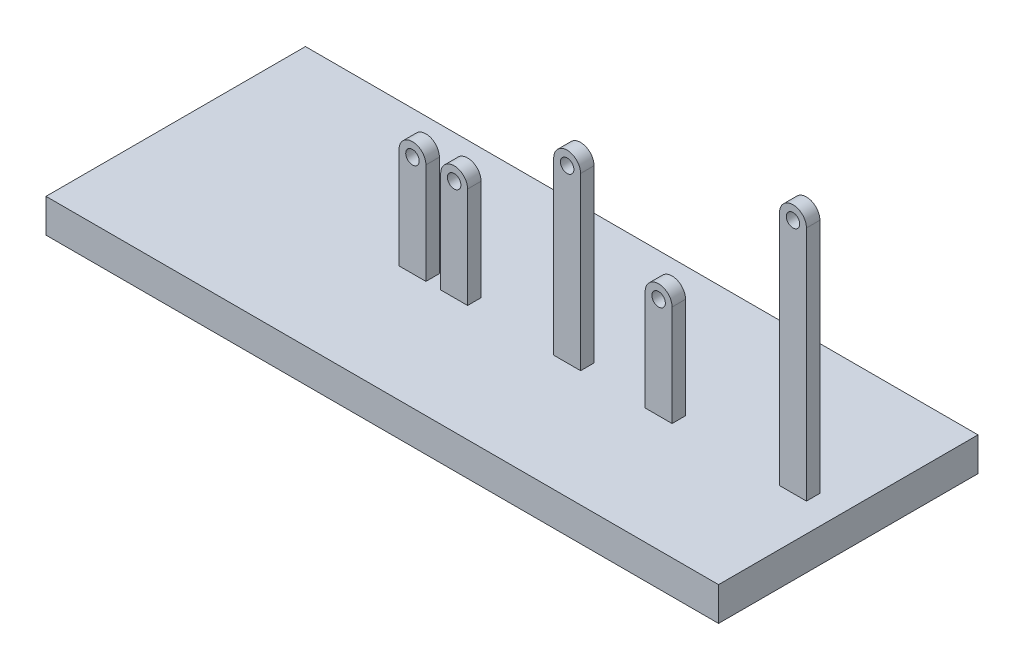
SolidWorks part; units mm, degrees
ref_plane "前基準面" through (0, 0, 0) normal (0, 0, 1) x (1, 0, 0)
ref_plane "上基準面" through (0, 0, 0) normal (0, 1, 0) x (1, 0, 0)
ref_plane "右基準面" through (0, 0, 0) normal (1, 0, 0) x (0, 0, -1)
sketch "草圖1" plane through (0, 0, 0) normal (0, 1, 0) x (1, 0, 0)
  line L1 (50, -19.288) -> (-50, -19.288)
  line L2 (50, -19.288) -> (50, 19.288)
  line L3 (50, 19.288) -> (-50, 19.288)
  line L4 (-50, -19.288) -> (-50, 19.288)
  line L5 (50, -19.288) -> (-50, 19.288) construction
  line L6 (50, 19.288) -> (-50, -19.288) construction
  point P0 (0, 0)
  dimension "D1" = 100
extrude "填料-伸長1" add sketch "草圖1" along normal blind 5
sketch "草圖2" plane through (0, 0, 0) normal (0, 0, 1) x (1, 0, 0)
  line L0 (-8.6, 20) -> (-8.6, 0)
  line L1 (-50, 0) -> (50, 0) construction
  line L2 (-8.6, 0) -> (-4.6, 0)
  line L3 (-4.6, 20) -> (-4.6, 0)
  line L4 (-14.8, 20) -> (-14.8, 0)
  line L5 (-10.8, 20) -> (-10.8, 0)
  line L6 (-14.8, 0) -> (-10.8, 0)
  line L7 (21.8, 20) -> (21.8, 0)
  line L8 (21.8, 0) -> (25.8, 0)
  line L9 (25.8, 20) -> (25.8, 0)
  line L10 (8.2, 30.4) -> (8.2, 0)
  line L11 (8.2, 0) -> (12.2, 0)
  line L12 (12.2, 30.4) -> (12.2, 0)
  line L13 (41.78, 40.17) -> (41.78, 0)
  line L14 (41.78, 0) -> (45.78, 0)
  line L15 (45.78, 40.17) -> (45.78, 0)
  arc A0 (-4.6, 20) -> (-8.6, 20) centre (-6.6, 20) ccw
  circle A1 centre (-6.6, 20) radius 1
  arc A2 (-10.8, 20) -> (-14.8, 20) centre (-12.8, 20) ccw
  circle A3 centre (-12.8, 20) radius 1
  arc A4 (25.8, 20) -> (21.8, 20) centre (23.8, 20) ccw
  circle A5 centre (23.8, 20) radius 1
  arc A6 (12.2, 30.4) -> (8.2, 30.4) centre (10.2, 30.4) ccw
  circle A7 centre (10.2, 30.4) radius 1
  arc A8 (45.78, 40.17) -> (41.78, 40.17) centre (43.78, 40.17) ccw
  circle A9 centre (43.78, 40.17) radius 1
  point P9 (0, 0)
  point P16 (-12.8, 15.1746)
  point P17 (-19.6112, 30.3883)
  point P24 (23.8, 0)
  point P38 (45.7681, 20.17)
  point P39 (41.6151, -0.2261)
  point P41 (10.2, 25.392)
  dimension "D1" = 2
  dimension "D2" = 2
  dimension "D4" = 2
  dimension "D5" = 2
  dimension "D9" = 2
  dimension "D10" = 2
  dimension "D18" = 2
  dimension "D19" = 2
  dimension "D20" = 2
  dimension "D21" = 2
  dimension "D3" = 6.6
  dimension "D6" = 0
  dimension "D7" = 12.8
  dimension "D8" = 20
  dimension "D11" = 0
  dimension "D12" = 20
  dimension "D13" = 23.8
  dimension "D14" = 0
  dimension "D15" = 10.2
  dimension "D16" = 0
  dimension "D17" = 43.78
  dimension "D22" = 10.4
extrude "填料-伸長2" add sketch "草圖2" along normal blind 2
